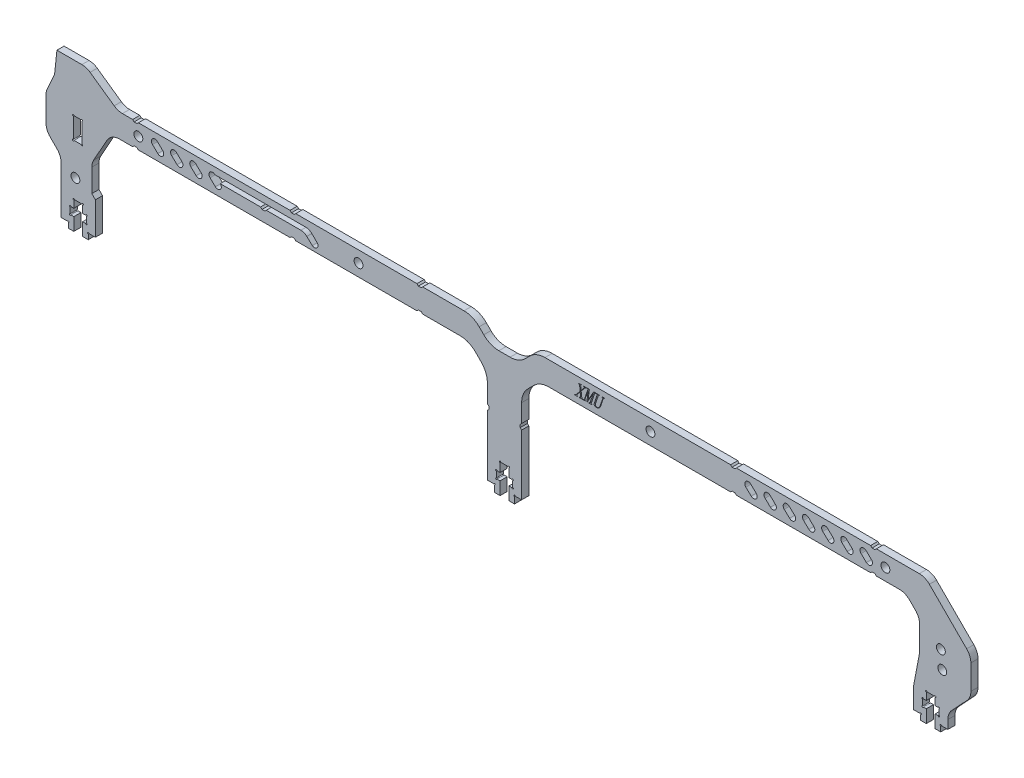
SolidWorks part; units mm, degrees
material "PPS"
ref_plane "前视基准面" through (0, 0, 0) normal (0, 0, 1) x (1, 0, 0)
ref_plane "上视基准面" through (0, 0, 0) normal (0, 1, 0) x (1, 0, 0)
ref_plane "右视基准面" through (0, 0, 0) normal (1, 0, 0) x (0, 0, -1)
sketch "草图1" plane through (0, 0, 0) normal (0, 0, 1) x (1, 0, 0)
  line L0 (-1000, 0) -> (49000, 0) construction
  line L1 (0, 0) -> (0, -218.3822) construction
  line L2 (6, -16.1697) -> (6, -48.75)
  line L3 (6, -48.75) -> (-6, -48.75) construction
  line L4 (-6, -16.1697) -> (-6, -48.75)
  line L5 (6, -48.75) -> (3.5, -48.75)
  line L6 (3.5, -48.75) -> (3.5, -51.25)
  line L7 (3.5, -51.25) -> (-3.5, -51.25) construction
  line L8 (-3.5, -48.75) -> (-3.5, -51.25)
  line L9 (-3.5, -48.75) -> (-6, -48.75)
  line L10 (1.55, -51.25) -> (1.55, -46.75)
  line L11 (1.55, -46.75) -> (2.85, -46.75)
  line L12 (2.85, -46.75) -> (2.85, -44.25)
  line L13 (2.85, -44.25) -> (1.55, -44.25)
  line L14 (1.55, -44.25) -> (1.55, -41)
  line L15 (1.55, -41) -> (-1.55, -41)
  line L16 (-1.55, -44.25) -> (-1.55, -41)
  line L17 (-2.85, -44.25) -> (-1.55, -44.25)
  line L18 (-2.85, -46.75) -> (-2.85, -44.25)
  line L19 (-1.55, -46.75) -> (-2.85, -46.75)
  line L20 (-1.55, -51.25) -> (-1.55, -46.75)
  line L21 (1.55, -51.25) -> (3.5, -51.25)
  line L22 (-1.55, -51.25) -> (-3.5, -51.25)
  line L23 (12.4197, -9.75) -> (6, -16.1697)
  line L24 (-12.4197, -9.75) -> (-6, -16.1697)
  line L25 (-147.7, -45.75) -> (-147.7, -41.25)
  line L26 (-150.8, -45.75) -> (-150.8, -41.25)
  line L27 (-147.7, -41.25) -> (-146.4, -41.25)
  line L28 (-146.4, -41.25) -> (-146.4, -38.75)
  line L29 (-146.4, -38.75) -> (-147.7, -38.75)
  line L30 (-147.7, -38.75) -> (-147.7, -36)
  line L31 (-150.8, -36) -> (-147.7, -36)
  line L32 (-150.8, -38.75) -> (-150.8, -36)
  line L33 (-152.1, -38.75) -> (-150.8, -38.75)
  line L34 (-152.1, -41.25) -> (-152.1, -38.75)
  line L35 (-150.8, -41.25) -> (-152.1, -41.25)
  line L36 (-5.0685, -7.5) -> (5.0685, -7.5)
  line L37 (5.0685, -7.5) -> (11.0685, -1.5)
  line L38 (11.0685, -1.5) -> (147.3211, -1.5)
  line L40 (145.3337, -25.5065) -> (145.3337, -14.709)
  line L41 (140.3747, -9.75) -> (12.4197, -9.75)
  line L42 (-5.0685, -7.5) -> (-11.0685, -1.5)
  line L44 (-11.0685, -1.5) -> (-157.5351, -1.5) construction
  line L45 (-137.7768, -9.75) -> (-12.4197, -9.75)
  line L50 (143.25, -36.4306) -> (143.25, -43.75)
  line L52 (155.25, -43.75) -> (143.25, -43.75) construction
  line L53 (155.25, -43.75) -> (152.75, -43.75)
  line L54 (152.75, -43.75) -> (152.75, -45.75)
  line L55 (152.75, -45.75) -> (145.75, -45.75) construction
  line L56 (145.75, -43.75) -> (145.75, -45.75)
  line L57 (145.75, -43.75) -> (143.25, -43.75)
  line L58 (150.8, -45.75) -> (150.8, -41.25)
  line L59 (150.8, -41.25) -> (152.1, -41.25)
  line L60 (152.1, -41.25) -> (152.1, -38.75)
  line L61 (152.1, -38.75) -> (150.8, -38.75)
  line L62 (150.8, -38.75) -> (150.8, -36)
  line L63 (150.8, -36) -> (147.7, -36)
  line L64 (147.7, -38.75) -> (147.7, -36)
  line L65 (146.4, -38.75) -> (147.7, -38.75)
  line L66 (146.4, -41.25) -> (146.4, -38.75)
  line L67 (147.7, -41.25) -> (146.4, -41.25)
  line L68 (147.7, -45.75) -> (147.7, -41.25)
  line L69 (150.8, -45.75) -> (152.75, -45.75)
  line L70 (147.7, -45.75) -> (145.75, -45.75)
  line L72 (57.6009, -1) -> (44.6221, -1) construction
  line L73 (145.3337, -25.5065) -> (143.25, -36.4306)
  line L74 (-147.7, -45.75) -> (-145.75, -45.75)
  line L75 (-150.8, -45.75) -> (-152.75, -45.75)
  line L76 (-152.75, -43.75) -> (-152.75, -45.75)
  line L77 (-155.25, -43.75) -> (-152.75, -43.75)
  line L78 (-145.75, -43.75) -> (-145.75, -45.75)
  line L79 (-145.75, -43.75) -> (-143.25, -43.75)
  line L80 (-157.5351, -1.5) -> (-160.547, -8.1912)
  line L81 (-160.547, -8.1912) -> (-160.547, -19.809)
  line L82 (-160.547, -19.809) -> (-155.25, -25.0873)
  line L87 (-143.25, -32.3726) -> (-144.5, -31.127)
  line L88 (-144.5, -31.127) -> (-144.5, -21.7902)
  line L89 (-144.5, -21.7902) -> (-137.7768, -9.75)
  line L90 (-155.25, -25.0873) -> (-155.25, -43.75)
  line L91 (-143.25, -32.3726) -> (-143.25, -43.75)
  line L92 (147.3211, -1.5) -> (163.2977, -17.4767)
  line L93 (163.2977, -17.4767) -> (163.2977, -30.1638)
  line L94 (163.2977, -30.1638) -> (155.25, -38.75)
  line L95 (155.25, -38.75) -> (155.25, -43.75)
  line L96 (-157.5351, -1.5) -> (-156.7241, 6.25)
  line L97 (-156.7241, 6.25) -> (-146.4, 6.25)
  line L98 (-146.4, 6.25) -> (-135.37, -1.5)
  line L99 (-135.37, -1.5) -> (-11.0685, -1.5)
  line L102 (140.3747, -9.75) -> (145.3337, -14.709)
  line L103 (56.6009, -9.75) -> (45.6221, -9.75) construction
  line L104 (146.1658, -18.25) -> (92.972, -18.25) construction
  line L105 (-154.7028, -11.25) -> (-130.7962, -11.25) construction
  circle A0 centre (-51.1115, -5.5) radius 1.55
  circle A1 centre (51.1115, -5.5) radius 1.55
  circle A5 centre (-51.1115, -5.5) radius 1.9051 construction
  circle A6 centre (51.1115, -5.5) radius 2.165 construction
  point P6 (0, -48.75)
  point P11 (0, -51.25)
  point P20 (0, -41)
  point P29 (-149.25, -36)
  point P43 (152.75, -44.75)
  point P78 (149.25, -36)
  dimension "D21" = 3.1
  dimension "D1" = 3.5
  dimension "D2" = 4.5
  dimension "D3" = 2.5
  dimension "D4" = 6
  dimension "D5" = 135
  dimension "D6" = 2.5
  dimension "D7" = 48.75
  dimension "D8" = 25.5
  dimension "D9" = 2
  dimension "D10" = 7
  dimension "D11" = 149.25
  dimension "D12" = 1.95
  dimension "D13" = 1.55
  dimension "D14" = 2.85
  dimension "D15" = 10.25
  dimension "D16" = 0.5
  dimension "D17" = 2.25
  dimension "D18" = 135
  dimension "D19" = 135
  dimension "D20" = 1.25
  dimension "D22" = 17.5
extrude "凸台-拉伸1" add sketch "草图1" along normal blind 2.5
sketch "草图2" plane through (0, 0, 0) normal (0, 0, 1) x (1, 0, 0)
  line L0 (98.8244, -4.7341) -> (98.8244, -1.5) construction
  line L2 (147.3211, -1.5) -> (11.0685, -1.5) construction
  line L4 (100.6889, -6.5159) -> (100.6889, -9.75) construction
  line L7 (12.4197, -9.75) -> (140.3747, -9.75) construction
  line L8 (94.8107, -5.6378) -> (97.9607, -5.6378) construction
  line L11 (86.3905, -7.4197) -> (84.526, -5.6378)
  line L16 (121.7047, -5.6122) -> (124.8547, -5.6122) construction
  line L17 (106.5671, -7.394) -> (104.7026, -5.6122)
  line L18 (104.7026, -5.6122) -> (106.4054, -3.8303) construction
  line L19 (106.4054, -3.8303) -> (108.27, -5.6122)
  line L20 (108.27, -5.6122) -> (106.5671, -7.394) construction
  line L21 (99.8252, -7.4197) -> (97.9607, -5.6378)
  line L22 (99.6881, -3.8303) -> (101.5526, -5.6122)
  line L23 (101.5526, -5.6122) -> (104.7026, -5.6122) construction
  line L24 (108.27, -5.6122) -> (111.42, -5.6122) construction
  line L25 (113.2845, -7.394) -> (111.42, -5.6122)
  line L26 (113.1228, -3.8303) -> (114.9873, -5.6122)
  line L27 (114.9873, -5.6122) -> (118.1373, -5.6122) construction
  line L28 (120.0018, -7.394) -> (118.1373, -5.6122)
  line L29 (119.8402, -3.8303) -> (121.7047, -5.6122)
  line L30 (126.7192, -7.394) -> (124.8547, -5.6122)
  line L31 (126.5819, -3.8048) -> (128.4464, -5.5866)
  line L32 (86.2289, -3.856) -> (88.0934, -5.6378)
  line L33 (88.0934, -5.6378) -> (91.2434, -5.6378) construction
  line L34 (93.1079, -7.4197) -> (91.2434, -5.6378)
  line L35 (92.9462, -3.856) -> (94.8107, -5.6378)
  line L36 (-106.2679, -5.6378) -> (-103.1179, -5.6378) construction
  line L38 (-112.9852, -5.6378) -> (-109.8352, -5.6378) construction
  line L39 (-121.4054, -7.4197) -> (-123.27, -5.6378)
  line L42 (-107.9707, -7.4197) -> (-109.8352, -5.6378)
  line L44 (-108.1324, -3.856) -> (-106.2679, -5.6378)
  line L47 (-101.2387, -7.4197) -> (-103.1032, -5.6378)
  line L48 (-101.4003, -3.856) -> (-99.5358, -5.6378) construction
  line L51 (-101.4003, -3.856) -> (-69.6149, -3.856)
  line L56 (-121.5671, -3.856) -> (-119.7026, -5.6378)
  line L57 (-119.7026, -5.6378) -> (-116.5526, -5.6378) construction
  line L58 (-114.6881, -7.4197) -> (-116.5526, -5.6378)
  line L59 (-114.8498, -3.856) -> (-112.9852, -5.6378)
  line L60 (-71.3031, -5.6378) -> (-99.5358, -5.6378)
  line L66 (-67.5422, -4.6871) -> (-65.6228, -6.5214)
  line L69 (-67.311, -8.3033) -> (-69.2304, -6.469)
  arc A10 (126.5819, -3.8048) -> (124.8547, -5.6122) centre (125.7183, -4.7085) ccw
  arc A11 (128.4464, -5.5866) -> (126.7192, -7.394) centre (127.5828, -6.4903) cw
  arc A12 (106.4054, -3.8303) -> (104.7026, -5.6122) centre (105.554, -4.7213) ccw
  arc A13 (108.27, -5.6122) -> (106.5671, -7.394) centre (107.4185, -6.5031) cw
  arc A14 (99.6881, -3.8303) -> (97.9607, -5.6378) centre (98.8244, -4.7341) ccw
  arc A15 (101.5526, -5.6122) -> (99.8252, -7.4197) centre (100.6889, -6.5159) cw
  arc A16 (113.1228, -3.8303) -> (111.42, -5.6122) centre (112.2714, -4.7213) ccw
  arc A17 (114.9873, -5.6122) -> (113.2845, -7.394) centre (114.1359, -6.5031) cw
  arc A18 (119.8402, -3.8303) -> (118.1373, -5.6122) centre (118.9887, -4.7213) ccw
  arc A19 (121.7047, -5.6122) -> (120.0018, -7.394) centre (120.8532, -6.5031) cw
  arc A20 (86.2289, -3.856) -> (84.526, -5.6378) centre (85.3774, -4.7469) ccw
  arc A21 (88.0934, -5.6378) -> (86.3905, -7.4197) centre (87.242, -6.5287) cw
  arc A22 (92.9462, -3.856) -> (91.2434, -5.6378) centre (92.0948, -4.7469) ccw
  arc A23 (94.8107, -5.6378) -> (93.1079, -7.4197) centre (93.9593, -6.5287) cw
  arc A34 (-121.5671, -3.856) -> (-123.27, -5.6378) centre (-122.4185, -4.7469) ccw
  arc A35 (-119.7026, -5.6378) -> (-121.4054, -7.4197) centre (-120.554, -6.5287) cw
  arc A36 (-114.8498, -3.856) -> (-116.5526, -5.6378) centre (-115.7012, -4.7469) ccw
  arc A37 (-112.9852, -5.6378) -> (-114.6881, -7.4197) centre (-113.8367, -6.5287) cw
  arc A38 (-108.1324, -3.856) -> (-109.8352, -5.6378) centre (-108.9838, -4.7469) ccw
  arc A39 (-106.2679, -5.6378) -> (-107.9707, -7.4197) centre (-107.1193, -6.5287) cw
  arc A40 (-101.4003, -3.856) -> (-103.1032, -5.6378) centre (-102.2518, -4.7469) ccw
  arc A41 (-99.5358, -5.6378) -> (-101.2387, -7.4197) centre (-100.3873, -6.5287) cw
  arc A46 (-71.3031, -5.6378) -> (-69.2304, -6.469) centre (-71.3031, -8.6378) cw
  arc A47 (-65.6228, -6.5214) -> (-67.311, -8.3033) centre (-66.548, -7.3355) cw
  arc A48 (-69.6149, -3.856) -> (-67.5422, -4.6871) centre (-69.6149, -6.856) cw
extrude "减重" cut sketch "草图2" against normal through all from surface at 2.5 starting at face at (-5.419, -33.6883, 2.5)
sketch "草图5" plane through (0, 0, 0) normal (0, 0, 1) x (1, 0, 0)
  line L0 (-123.27, -5.6378) -> (-121.4054, -7.4197) construction
  line L1 (-126.42, -5.6378) -> (-123.27, -5.6378) construction
  line L2 (-126.42, -5.6378) -> (-128.2845, -3.856) construction
  line L3 (-128.1228, -7.4197) -> (-129.9873, -5.6378) construction
  line L4 (-129.1359, -4.7469) -> (-127.2714, -6.5287) construction
  line L5 (132.4479, -4.6957) -> (134.3124, -6.4776) construction
  line L9 (128.4464, -5.5866) -> (131.5964, -5.5866) construction
  line L10 (135.1638, -5.5866) -> (133.2993, -3.8048) construction
  line L11 (133.4609, -7.3685) -> (131.5964, -5.5866) construction
  arc A1 (-126.42, -5.6378) -> (-128.1228, -7.4197) centre (-127.2714, -6.5287) cw construction
  arc A2 (-129.9873, -5.6378) -> (-128.2845, -3.856) centre (-129.1359, -4.7469) cw construction
  arc A7 (135.1638, -5.5866) -> (133.4609, -7.3685) centre (134.3124, -6.4776) cw construction
  arc A8 (131.5964, -5.5866) -> (133.2993, -3.8048) centre (132.4479, -4.6957) cw construction
  circle A9 centre (-128.2036, -5.6378) radius 1.55
  circle A11 centre (133.3801, -5.5866) radius 1.55
  dimension "D1" = 3.1
extrude "光球接口" cut sketch "草图5" along normal through all
sketch "草图3" plane through (0, 0, 2.5) normal (0, 0, 1) x (1, 0, 0)
  text T0 "XMU" font "宋体" height 4.25
extrude "切除-拉伸3" cut sketch "草图3" against normal through all
sketch "草图4" plane through (0, 0, 0) normal (0, 0, 1) x (1, 0, 0)
  line L0 (-6, -25.591) -> (-5.5, -26.091)
  line L1 (-6, -16.1697) -> (-6, -48.75) construction
  line L2 (-5.5, -26.091) -> (-5.5, -27.091)
  line L3 (-5.5, -27.091) -> (-6, -27.591)
  line L4 (-6, -27.591) -> (-6, -25.591)
  line L5 (0, 0) -> (0, -67.6388) construction
  line L6 (6, -27.591) -> (6, -25.591)
  line L7 (5.5, -27.091) -> (6, -27.591)
  line L8 (5.5, -26.091) -> (5.5, -27.091)
  line L9 (6, -25.591) -> (5.5, -26.091)
  line L18 (-11.0685, -1.5) -> (-135.37, -1.5) construction
  line L19 (-128.2051, -1.5) -> (-130.2051, -1.5)
  line L20 (-128.7051, -2) -> (-128.2051, -1.5)
  line L21 (-129.7051, -2) -> (-128.7051, -2)
  line L22 (-130.2051, -1.5) -> (-129.7051, -2)
  line L23 (0, 0) -> (-134.5835, 0) construction
  line L36 (-137.7768, -9.75) -> (-12.4197, -9.75) construction
  line L41 (-99.5358, -5.6378) -> (-71.3031, -5.6378) construction
  line L46 (130.2051, -1.5) -> (129.7051, -2)
  line L47 (129.7051, -2) -> (128.7051, -2)
  line L48 (128.7051, -2) -> (128.2051, -1.5)
  line L49 (128.2051, -1.5) -> (130.2051, -1.5)
  line L50 (-135.37, -1.5) -> (-135.37, -9.75) construction
  line L51 (-1135.37, -5.625) -> (48864.63, -5.625) construction
  line L52 (-130.2051, -9.75) -> (-129.7051, -9.25)
  line L53 (-129.7051, -9.25) -> (-128.7051, -9.25)
  line L54 (-128.7051, -9.25) -> (-128.2051, -9.75)
  line L55 (-128.2051, -9.75) -> (-130.2051, -9.75)
  line L64 (-73.0982, -1.5) -> (-75.0982, -1.5)
  line L65 (-73.5982, -2) -> (-73.0982, -1.5)
  line L66 (-74.5982, -2) -> (-73.5982, -2)
  line L67 (-75.0982, -1.5) -> (-74.5982, -2)
  line L68 (-75.0982, -9.75) -> (-74.5982, -9.25)
  line L69 (-74.5982, -9.25) -> (-73.5982, -9.25)
  line L70 (-73.5982, -9.25) -> (-73.0982, -9.75)
  line L71 (-73.0982, -9.75) -> (-75.0982, -9.75)
  line L72 (-28.6523, -1.5) -> (-30.6523, -1.5)
  line L73 (-29.1523, -2) -> (-28.6523, -1.5)
  line L74 (-30.1523, -2) -> (-29.1523, -2)
  line L75 (-30.6523, -1.5) -> (-30.1523, -2)
  line L76 (-30.6523, -9.75) -> (-30.1523, -9.25)
  line L77 (-30.1523, -9.25) -> (-29.1523, -9.25)
  line L78 (-29.1523, -9.25) -> (-28.6523, -9.75)
  line L79 (-28.6523, -9.75) -> (-30.6523, -9.75)
  line L80 (-83.4194, -5.6378) -> (-85.4194, -5.6378)
  line L81 (-83.9194, -6.1378) -> (-83.4194, -5.6378)
  line L82 (-84.9194, -6.1378) -> (-83.9194, -6.1378)
  line L83 (-85.4194, -5.6378) -> (-84.9194, -6.1378)
  line L92 (79.1823, -9.75) -> (81.1823, -9.75)
  line L93 (128.2051, -9.75) -> (130.2051, -9.75)
  line L94 (128.7051, -9.25) -> (128.2051, -9.75)
  line L95 (129.7051, -9.25) -> (128.7051, -9.25)
  line L96 (130.2051, -9.75) -> (129.7051, -9.25)
  line L97 (-151, -10.625) -> (-148, -10.625)
  line L98 (-148, -10.625) -> (-148, -18.125)
  line L99 (-148, -18.125) -> (-151, -18.125)
  line L100 (-151, -18.125) -> (-151, -10.625)
  line L101 (79.6823, -9.25) -> (79.1823, -9.75)
  line L102 (80.6823, -9.25) -> (79.6823, -9.25)
  line L103 (81.1823, -9.75) -> (80.6823, -9.25)
  line L104 (81.1823, -1.5) -> (80.6823, -2)
  line L105 (80.6823, -2) -> (79.6823, -2)
  line L106 (79.6823, -2) -> (79.1948, -1.5)
  line L107 (79.1948, -1.5) -> (81.1823, -1.5)
  line L108 (147.3211, -1.5) -> (11.0685, -1.5) construction
  line L109 (163.2977, -30.1638) -> (163.2977, -17.4767) construction
  line L110 (-144.5, -31.127) -> (-144.5, -21.7902) construction
  line L112 (-155.25, -43.75) -> (-152.75, -43.75) construction
  circle A0 centre (-150.25, -29.25) radius 1.55
  circle A1 centre (152.7976, -20.675) radius 1.55
  circle A2 centre (153.2976, -26.6541) radius 1.55
  point P4 (-6, -26.591)
  point P19 (-85.4194, -5.6378)
  point P49 (-135.37, -5.625)
  dimension "D13" = 3.1
  dimension "D20" = 3.1
  dimension "D1" = 45
  dimension "D2" = 0.5
  dimension "D3" = 1
  dimension "D4" = 45
  dimension "D5" = 0.5
  dimension "D6" = 1
  dimension "D7" = 45
  dimension "D8" = 1
  dimension "D9" = 6
  dimension "D10" = 15.05
  dimension "D11" = 10.0002
  dimension "D12" = 0.5
  dimension "D14" = 5
  dimension "D15" = 7.5
  dimension "D16" = 3
  dimension "D17" = 14.5
  dimension "D18" = 3.5
  dimension "D19" = 5.75
extrude "线槽和设备接口" cut sketch "草图4" along normal through all
fillet "圆角2" radius 5 16 edges at (155.25, -38.75, 1.25) (145.3337, -25.5065, 1.25) (143.25, -36.4306, 1.25) (147.3211, -1.5, 1.25) (163.2977, -30.1638, 1.25) (163.2977, -17.4767, 1.25) (145.3337, -14.709, 1.25) (140.3747, -9.75, 1.25) (-137.7768, -9.75, 1.25) (-144.5, -21.7902, 1.25) (-146.4, 6.25, 1.25) (-155.25, -25.0873, 1.25) (-160.547, -19.809, 1.25) (-160.547, -8.1912, 1.25) (-157.5351, -1.5, 1.25) (-135.37, -1.5, 1.25)
fillet "圆角3" radius 7.5 8 edges at (12.4197, -9.75, 1.25) (6, -16.1697, 1.25) (-6, -16.1697, 1.25) (-12.4197, -9.75, 1.25) (11.0685, -1.5, 1.25) (5.0685, -7.5, 1.25) (-5.0685, -7.5, 1.25) (-11.0685, -1.5, 1.25)
sketch "草图6" plane through (0, 0, 2.5) normal (0, 0, 1) x (1, 0, 0)
  line L0 (0, 0) -> (0, -63.5679) construction
  circle A0 centre (-151, -10.625) radius 0.25
  circle A1 centre (-148, -10.625) radius 0.25
  circle A2 centre (-151, -18.125) radius 0.25
  circle A3 centre (-148, -18.125) radius 0.25
  circle A4 centre (-150.8, -36) radius 0.25
  circle A5 centre (-147.7, -36) radius 0.25
  circle A6 centre (-152.1, -38.75) radius 0.25
  circle A7 centre (-152.1, -41.25) radius 0.25
  circle A8 centre (-146.4, -38.75) radius 0.25
  circle A9 centre (-146.4, -41.25) radius 0.25
  circle A10 centre (-2.85, -44.25) radius 0.25
  circle A11 centre (-2.85, -46.75) radius 0.25
  circle A12 centre (-1.55, -41) radius 0.25
  circle A13 centre (-3.5, -48.75) radius 0.25
  circle A15 centre (-152.75, -43.75) radius 0.25
  circle A16 centre (-145.75, -43.75) radius 0.25
  circle A17 centre (145.75, -43.75) radius 0.25
  circle A18 centre (152.75, -43.75) radius 0.25
  circle A19 centre (3.5, -48.75) radius 0.25
  circle A20 centre (1.55, -41) radius 0.25
  circle A21 centre (2.85, -46.75) radius 0.25
  circle A22 centre (2.85, -44.25) radius 0.25
  circle A23 centre (146.4, -41.25) radius 0.25
  circle A24 centre (146.4, -38.75) radius 0.25
  circle A25 centre (152.1, -41.25) radius 0.25
  circle A26 centre (152.1, -38.75) radius 0.25
  circle A27 centre (147.7, -36) radius 0.25
  circle A28 centre (150.8, -36) radius 0.25
  dimension "D1" = 0.5
extrude "直角约束" cut sketch "草图6" against normal through all
